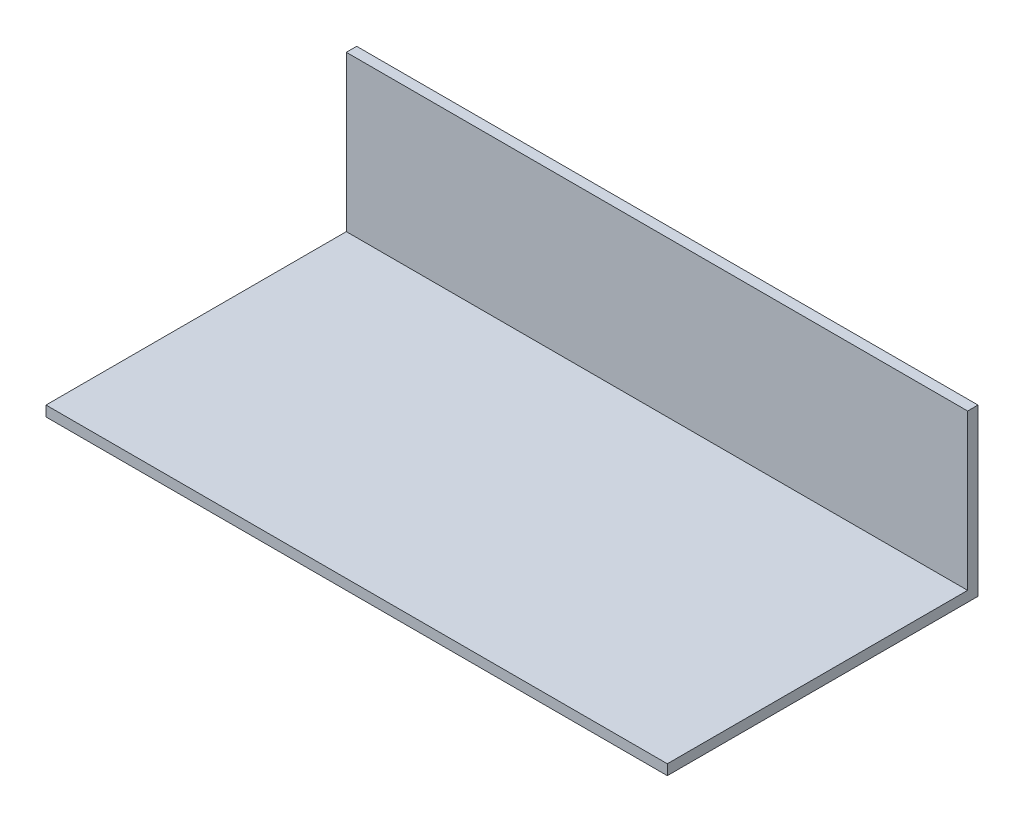
SolidWorks part; units mm, degrees
ref_plane "Front Plane" through (0, 0, 0) normal (0, 0, 1) x (1, 0, 0)
ref_plane "Top Plane" through (0, 0, 0) normal (0, 1, 0) x (1, 0, 0)
ref_plane "Right Plane" through (0, 0, 0) normal (1, 0, 0) x (0, 0, -1)
sketch "Sketch1" plane through (0, 0, 0) normal (0, 1, 0) x (1, 0, 0)
  line L1 (-300, -150) -> (300, -150)
  line L2 (-300, -150) -> (-300, 150)
  line L3 (-300, 150) -> (300, 150)
  line L4 (300, -150) -> (300, 150)
  line L5 (-300, -150) -> (300, 150) construction
  line L6 (-300, 150) -> (300, -150) construction
  point P0 (0, 0)
  dimension "D1" = 600
  dimension "D2" = 300
extrude "Boss-Extrude1" add sketch "Sketch1" along normal blind 10
sketch "Sketch2" plane through (0, 10, 0) normal (0, 1, 0) x (1, 0, 0)
  line L0 (300, -150) -> (300, 150) construction
  line L1 (-300, 150) -> (300, 150)
  line L2 (-300, 150) -> (-300, 140)
  line L3 (-300, 140) -> (300, 140)
  line L4 (300, 150) -> (300, 140)
  dimension "D1" = 10
extrude "Boss-Extrude2" add sketch "Sketch2" along normal blind 150
